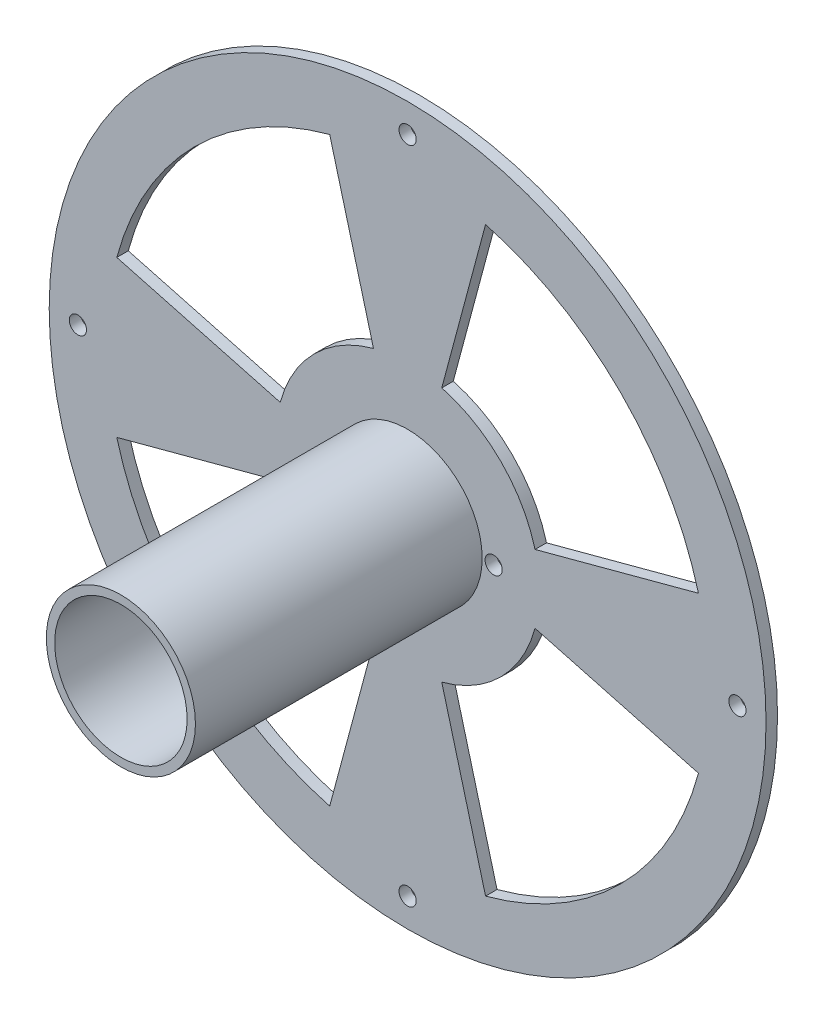
SolidWorks part; units mm, degrees
ref_plane "Front" through (0, 0, 0) normal (0, 0, 1) x (1, 0, 0)
ref_plane "Top" through (0, 0, 0) normal (0, 1, 0) x (1, 0, 0)
ref_plane "Right" through (0, 0, 0) normal (1, 0, 0) x (0, 0, -1)
sketch "Sketch1" plane through (0, 0, 0) normal (0, 0, 1) x (1, 0, 0)
  line L0 (0, 0) -> (-62.5, 0) construction
  line L1 (0, 0) -> (0, 10.457) construction
  circle A0 centre (0, 0) radius 62.5
  circle A1 centre (-57.5, 0) radius 1.5
  circle A2 centre (0, 57.5) radius 1.5
  circle A3 centre (57.5, 0) radius 1.5
  circle A4 centre (0, -57.5) radius 1.5
  circle A5 centre (-15, 0) radius 1.5
  circle A6 centre (15, 0) radius 1.5
  point P15 (0, 0)
  dimension "D1" = 125
  dimension "D4" = 15
  dimension "D3" = 4
extrude "Boss-Extrude1" add sketch "Sketch1" along normal blind 2
sketch "Sketch2" plane through (0, 0, 2) normal (0, 0, 1) x (1, 0, 0)
  circle A0 centre (0, 0) radius 13
extrude "Boss-Extrude2" add sketch "Sketch2" along normal blind 50
sketch "Sketch6" plane through (0, 0, 52) normal (0, 0, 1) x (1, 0, 0)
  line L0 (0, 0) -> (13, 0) construction
  line L1 (13, 0) -> (-13, 0) construction
  circle A0 centre (0, 0) radius 11.55
  circle A2 centre (0, 0) radius 13 construction
extrude "Cut-Extrude7" cut sketch "Sketch6" against normal blind 47
sketch "Sketch7" plane through (0, 0, 5) normal (0, 0, 1) x (1, 0, 0)
  circle A0 centre (0, 0) radius 10
extrude "Cut-Extrude8" cut sketch "Sketch7" against normal through all contours A0
sketch "Sector (Cut Extrude)" plane through (0, 0, 2) normal (0, 0, 1) x (1, 0, 0)
  line L0 (0, 0) -> (0, -62.5) construction
  line L1 (62.5, 0) -> (0, 0) construction
  line L2 (22.2163, -5.9528) -> (50.7111, -13.588)
  line L3 (-22.2163, -5.9528) -> (-50.7111, -13.588)
  line L4 (5.9528, -22.2163) -> (13.588, -50.7111)
  line L5 (-5.9528, -22.2163) -> (-13.588, -50.7111)
  line L6 (-5.9528, 22.2163) -> (-13.588, 50.7111)
  line L7 (-22.2163, 5.9528) -> (-50.7111, 13.588)
  line L8 (22.2163, 5.9528) -> (50.7111, 13.588)
  line L9 (5.9528, 22.2163) -> (13.588, 50.7111)
  line L10 (0, 0) -> (50.7111, -13.588) construction
  line L11 (0, 0) -> (13.588, -50.7111) construction
  circle A0 centre (0, 0) radius 62.5 construction
  arc A1 (5.9528, -22.2163) -> (22.2163, -5.9528) centre (0, 0) ccw
  arc A2 (13.588, -50.7111) -> (50.7111, -13.588) centre (0, 0) ccw
  arc A3 (-22.2163, -5.9528) -> (-5.9528, -22.2163) centre (0, 0) ccw
  arc A4 (-50.7111, -13.588) -> (-13.588, -50.7111) centre (0, 0) ccw
  arc A5 (-5.9528, 22.2163) -> (-22.2163, 5.9528) centre (0, 0) ccw
  arc A6 (-13.588, 50.7111) -> (-50.7111, 13.588) centre (0, 0) ccw
  arc A7 (22.2163, 5.9528) -> (5.9528, 22.2163) centre (0, 0) ccw
  arc A8 (50.7111, 13.588) -> (13.588, 50.7111) centre (0, 0) ccw
  circle A9 centre (0, 0) radius 13 construction
  point P25 (0, 0)
  dimension "D1" = 4
  dimension "D2" = 10
  dimension "D3" = 10
  dimension "D4" = 15
  dimension "D5" = 15
extrude "Cut-Extrude9" cut sketch "Sector (Cut Extrude)" against normal through all
